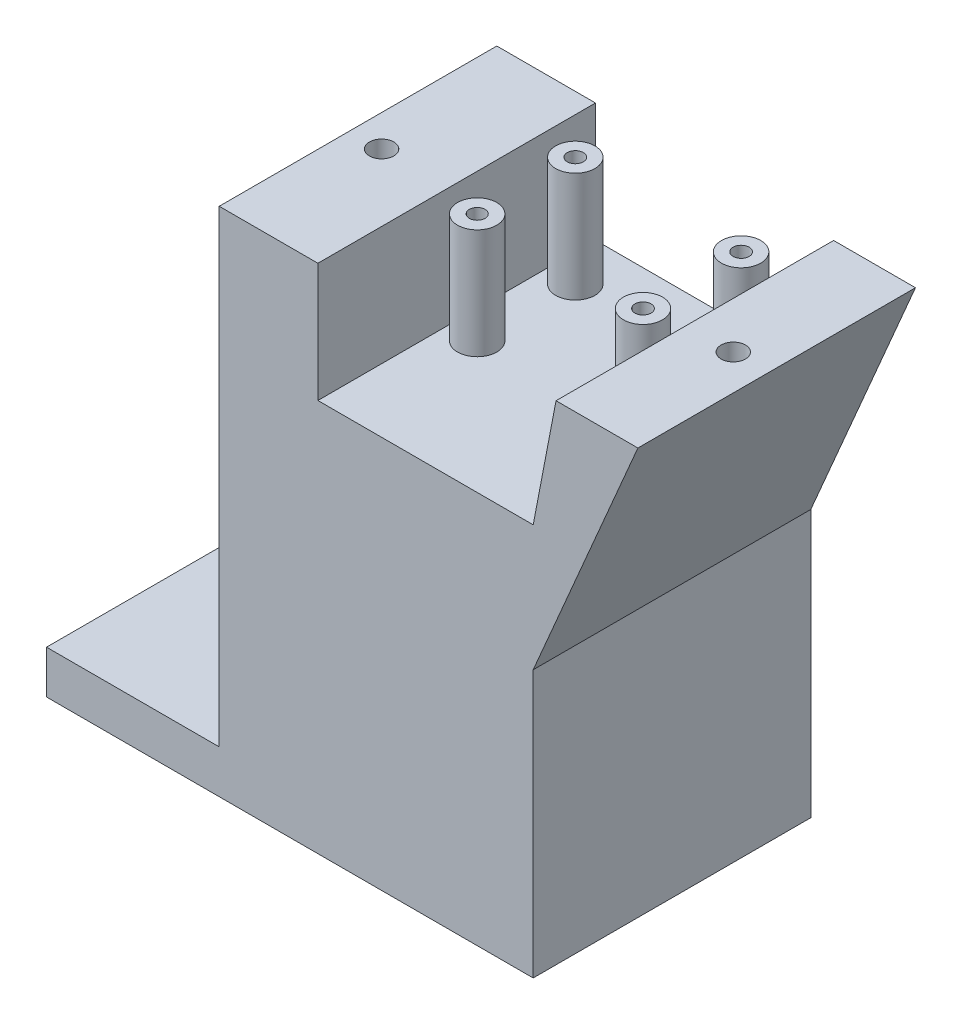
SolidWorks part; units mm, degrees
ref_plane "Front Plane" through (0, 0, 0) normal (0, 0, 1) x (1, 0, 0)
ref_plane "Top Plane" through (0, 0, 0) normal (0, 1, 0) x (1, 0, 0)
ref_plane "Right Plane" through (0, 0, 0) normal (1, 0, 0) x (0, 0, -1)
sketch "Sketch1" plane through (0, 0, 0) normal (0, 1, 0) x (1, 0, 0)
  line L1 (-12.7693, -20.6272) -> (27.2307, -20.6272)
  line L2 (-12.7693, -20.6272) -> (-12.7693, 14.7358)
  line L3 (-12.7693, 14.7358) -> (27.2307, 14.7358)
  line L4 (27.2307, -20.6272) -> (27.2307, 14.7358)
  dimension "D1" = 35.363
  dimension "D2" = 40
extrude "Boss-Extrude1" add sketch "Sketch1" along normal blind 50
sketch "Sketch2" plane through (-12.7693, 0, 0) normal (-1, 0, 0) x (0, 0, 1)
  line L0 (-14.7358, 50) -> (-14.7358, 0) construction
  line L1 (-14.7358, 5.5) -> (20.6272, 5.5)
  line L2 (-14.7358, 5.5) -> (-14.7358, 0)
  line L3 (-14.7358, 0) -> (20.6272, 0)
  line L4 (20.6272, 5.5) -> (20.6272, 0)
  line L5 (20.6272, 50) -> (20.6272, 0) construction
  line L6 (-14.7358, 0) -> (20.6272, 0) construction
  dimension "D1" = 5.5
extrude "Boss-Extrude2" add sketch "Sketch2" along normal blind 22
sketch "Sketch3" plane through (0, 50, 0) normal (0, 1, 0) x (1, 0, 0)
  line L0 (27.2307, -20.6272) -> (27.2307, 14.7358) construction
  line L1 (27.2307, 14.7358) -> (-12.7693, 14.7358) construction
  circle A0 centre (3.3557, -3.8892) radius 2.5
  circle A1 centre (24.3557, -3.7642) radius 2.5
  circle A2 centre (3.3557, 8.6108) radius 2.5
  circle A3 centre (24.3553, 8.7358) radius 2.5
  circle A4 centre (3.3557, -3.8892) radius 1
  circle A5 centre (24.3557, -3.7642) radius 1.025
  circle A6 centre (24.3553, 8.7358) radius 1.025
  circle A7 centre (3.3557, 8.6108) radius 1.025
  dimension "D1" = 5
  dimension "D2" = 2
  dimension "D9" = 6.125
  dimension "D10" = 6
  dimension "D3" = 12.5
  dimension "D4" = 21
  dimension "D5" = 12.5
  dimension "D6" = 21
  dimension "D8" = 2.875
extrude "Boss-Extrude3" add sketch "Sketch3" along normal blind 14
sketch "Sketch6" plane through (0, 0, 0) normal (0, -1, 0) x (-1, 0, 0)
  line L1 (34.7693, 14.7358) -> (34.7693, -20.6272) construction
  point P0 (24.7693, -2.9457)
  point P21 (34.7693, -2.9457)
  dimension "D1" = 10
hole_wizard "Dégagement M71" positions "Sketch6" profile "Sketch5" hole size "M7" standard "ISO" end condition through all
sketch "Sketch5" plane through (-24.7693, 0, 2.9457) normal (1, 0, 0) x (0, 0, -1)
  line L0 (0, 0) -> (0, 64)
  line L1 (0, 64) -> (4, 64)
  line L2 (4, 64) -> (4, 0)
  line L5 (4, 0) -> (0, 0)
  line L11 (0, -6.35) -> (0, 107.95) construction
  dimension "Thru Hole Dia." = 8
  dimension "Thru Hole Depth" = 64
sketch "Sketch7" plane through (0, 0, 20.6272) normal (0, 0, 1) x (1, 0, 0)
  line L0 (27.2307, 34.0105) -> (40.5686, 65.1441)
  line L1 (40.5686, 65.1441) -> (30.1399, 65.1441)
  line L2 (30.1399, 65.1441) -> (27.2307, 50)
  line L3 (27.2307, 50) -> (27.2307, 0) construction
  line L4 (27.2307, 50) -> (27.2307, 34.0105)
  line L5 (-12.7693, 50) -> (27.2307, 50) construction
extrude "Boss-Extrude4" add sketch "Sketch7" against normal up to vertex (35.363 mm away)
sketch "Sketch8" plane through (0, 50, 0) normal (0, 1, 0) x (1, 0, 0)
  line L0 (-12.7693, 14.7358) -> (-12.7693, -20.6272) construction
  line L1 (-12.7693, -20.6272) -> (-0.1973, -20.6272)
  line L2 (-12.7693, -20.6272) -> (-12.7693, 14.7358)
  line L3 (-12.7693, 14.7358) -> (-0.1973, 14.7358)
  line L4 (-0.1973, -20.6272) -> (-0.1973, 14.7358)
  line L5 (-12.7693, -20.6272) -> (27.2307, -20.6272) construction
  line L6 (27.2307, 14.7358) -> (-12.7693, 14.7358) construction
extrude "Boss-Extrude5" add sketch "Sketch8" along normal up to surface (15.1441 mm away) up to face at (35.3542, 65.1441, 2.9457)
sketch "Sketch11" plane through (0, 65.1441, 0) normal (0, 1, 0) x (1, 0, 0)
  line L0 (3.3557, -3.8892) -> (24.3557, -3.7642) construction
  point P0 (-8.7453, -3.9613)
  point P2 (36.0547, -3.9613)
  dimension "D1" = 44.8
hole_wizard "Dégagement M2.53" positions "Sketch11" profile "Sketch12" hole size "M2.5" standard "ISO"
sketch "Sketch12" plane through (-8.7453, 65.1441, 3.9613) normal (1, 0, 0) x (0, 0, 1)
  line L0 (0, 0) -> (0, 6.9313)
  line L1 (0, 6.9313) -> (1.55, 6)
  line L2 (1.55, 6) -> (1.55, 0)
  line L5 (1.55, 0) -> (0, 0)
  line L10 (0, 6.9313) -> (-1.55, 6) construction
  line L11 (0, -6.35) -> (0, 107.95) construction
  dimension "Hole Dia." = 3.1
  dimension "Hole Depth" = 6
  dimension "Drill Angle" = 118
sketch "Sketch15" plane through (0, 0, 0) normal (0, -1, 0) x (-1, 0, 0)
  line L0 (-27.2307, 14.7358) -> (-27.2307, -20.6272) construction
  line L1 (-27.2307, -20.6272) -> (-27.2307, 14.7358) construction
  point P0 (8.4737, -2.9457)
  point P3 (-20.2307, -2.9457)
  point P8 (-27.2307, -2.9457)
  dimension "D1" = 7
  dimension "D2" = 28.7044
hole_wizard "Dégagement M2.51" positions "Sketch15" profile "Sketch14" hole size "M2.5" standard "ISO"
sketch "Sketch14" plane through (-8.4737, 0, 2.9457) normal (1, 0, 0) x (0, 0, -1)
  line L0 (0, 0) -> (0, 6.9313)
  line L1 (0, 6.9313) -> (1.55, 6)
  line L2 (1.55, 6) -> (1.55, 0)
  line L5 (1.55, 0) -> (0, 0)
  line L10 (0, 6.9313) -> (-1.55, 6) construction
  line L11 (0, -6.35) -> (0, 107.95) construction
  dimension "Hole Dia." = 3.1
  dimension "Hole Depth" = 6
  dimension "Drill Angle" = 118
